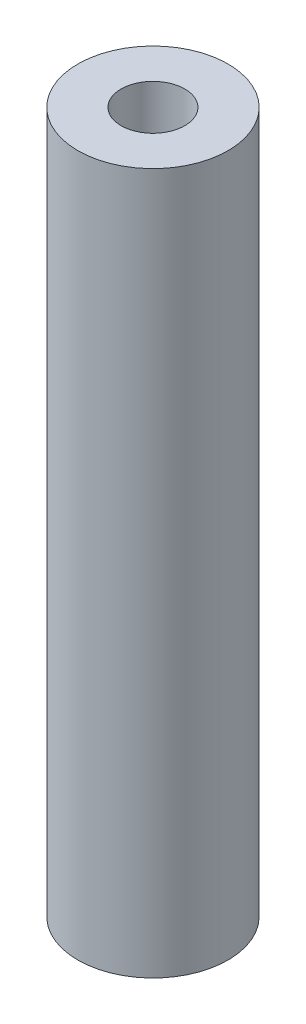
SolidWorks part; units mm, degrees
material "6061 Alloy"
ref_plane "Front Plane" through (0, 0, 0) normal (0, 0, 1) x (1, 0, 0)
ref_plane "Top Plane" through (0, 0, 0) normal (0, 1, 0) x (1, 0, 0)
ref_plane "Right Plane" through (0, 0, 0) normal (1, 0, 0) x (0, 0, -1)
sketch "Sketch1" plane through (0, 0, 0) normal (0, 1, 0) x (1, 0, 0)
  circle A0 centre (0, 0) radius 2.0193
  circle A1 centre (0, 0) radius 4.7625
  dimension "D1" = 4.0386
  dimension "D2" = 9.525
extrude "Boss-Extrude1" add sketch "Sketch1" along normal blind 44.45
